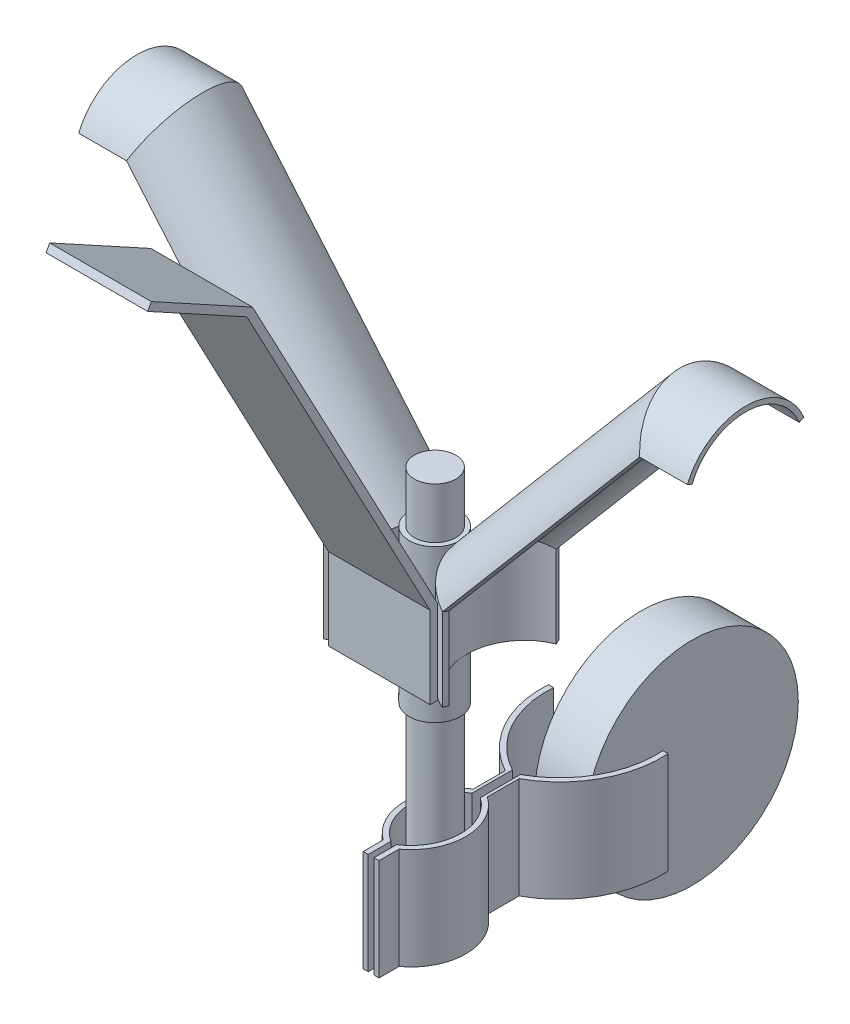
SolidWorks part; units mm, degrees
ref_plane "Front Plane" through (0, 0, 0) normal (0, 0, 1) x (1, 0, 0)
ref_plane "Top Plane" through (0, 0, 0) normal (0, 1, 0) x (1, 0, 0)
ref_plane "Right Plane" through (0, 0, 0) normal (1, 0, 0) x (0, 0, -1)
sketch "Sketch1" plane through (0, 0, 270) normal (0, 0, -1) x (-1, 0, 0)
  line L0 (-59.894, -72.5) -> (-47.401, -72.5)
  line L1 (-59.894, -72.5) -> (59.894, -72.5) construction
  line L2 (-47.401, -72.5) -> (-5, -122.5058)
  line L3 (-5, -122.5058) -> (-5, -141.2421)
  line L4 (0, 0) -> (0, -209.7536) construction
  dimension "D1" = 5
ref_plane "Plane1" through (59.894, -72.5, 270) normal (-1, 0, 0) x (0, 0, 1)
sketch "Sketch2" plane through (59.894, -72.5, 270) normal (-1, 0, 0) x (0, 0, 1)
  line L0 (-11.4645, -6.6719) -> (-10.5401, -7.0533)
  line L1 (11.4645, -6.6719) -> (10.5401, -7.0533)
  arc A0 (-10.5401, -7.0533) -> (10.5401, -7.0533) centre (0, -11.402) cw
  arc A1 (-11.4645, -6.6719) -> (11.4645, -6.6719) centre (0, -11.402) cw
  arc A2 (-2.292, -0.2327) -> (10.5401, -7.0533) centre (0, -11.402) cw construction
  arc A3 (-2.493, 0.7468) -> (11.4645, -6.6719) centre (0, -11.402) cw construction
  point P3 (0, 0)
  dimension "D1" = 1
sweep "Sweep1" add profiles "Sketch2" path "Sketch1"
sketch "Sketch3" plane through (0, 0, 0) normal (1, 0, 0) x (0, 0, -1)
  line L0 (-337.4206, -45.7822) -> (-317.7187, -56.5618)
  line L1 (-317.7187, -56.5618) -> (-281.4645, -124.9537)
  line L2 (-281.4645, -124.9537) -> (-281.4645, -141.2421)
  spline S0 degree 3 poles (-258, -72.5) (-288.1874, -72.5) (-335.6417, -49.6062) (-373.8553, -21.3954) (-386.923, -8.5304) knots -0.01 -0.01 -0.01 -0.01 0.619347 0.99 0.99 0.99 0.99 construction
extrude "Extrude-Thin1" add sketch "Sketch3" along normal mid plane 20 separate body thin thin type mid plane wall 1.5
sketch "Sketch4" plane through (0, -141.2421, 0) normal (0, -1, 0) x (1, 0, 0)
  line L0 (0, 385.5199) -> (0, -463.4767) construction
  circle A0 centre (0, 271.3071) radius 4
  circle A1 centre (0, 271.3071) radius 5
  dimension "D1" = 8
  dimension "D2" = 1
extrude "Boss-Extrude1" add sketch "Sketch4" along normal blind 10 and the other way blind 20
mirror "Mirror1" about plane through (0, 0, 0) normal (1, 0, 0) of "Sweep1"
sketch "Sketch5" plane through (0, -121.2421, 0) normal (0, 1, 0) x (1, 0, 0)
  line L0 (0, -385.5199) -> (0, 463.4767) construction
  circle A0 centre (0, -271.2258) radius 4.0812
extrude "Boss-Extrude2" add sketch "Sketch5" along normal blind 10 and the other way blind 70
sketch "Sketch6" plane through (0, -191.2421, 0) normal (0, -1, 0) x (1, 0, 0)
  line L0 (-11.768, 237.1512) -> (-10.768, 237.1512)
  line L1 (-1.3629, 260.45) -> (-1.3629, 265.95) construction
  line L2 (0, 276.3071) -> (0, 266.3071) construction
  line L3 (0, 385.5199) -> (0, -463.4767) construction
  line L4 (-0.5609, 279.3642) -> (-0.5609, 283.8196)
  line L5 (-0.5609, 283.8196) -> (-1.5609, 283.8196)
  line L6 (-1.5609, 283.8196) -> (-1.5609, 279.8891)
  line L7 (-1.5609, 279.8891) -> (-1.5609, 279.8891)
  line L8 (-1.5609, 279.8891) -> (-1.5609, 279.8891)
  line L9 (-1.5609, 279.8891) -> (-1.5609, 279.8891)
  line L10 (-1.5609, 283.8196) -> (-1.5609, 280.8891) construction
  line L11 (-0.7929, 263.1264) -> (-0.7929, 255.2322)
  line L12 (-1.3629, 262.3048) -> (-1.3629, 256.0539)
  line L13 (11.768, 237.1512) -> (10.768, 237.1512)
  line L14 (1.3628, 262.3048) -> (1.3628, 256.0539)
  line L15 (0.7928, 263.1264) -> (0.7928, 255.2322)
  line L16 (0.5609, 283.8196) -> (1.5609, 283.8196)
  line L17 (1.5609, 283.8196) -> (1.5609, 279.8891)
  line L18 (0.5609, 279.3642) -> (0.5609, 283.8196)
  arc A0 (-0.5609, 279.3642) -> (-0.7929, 263.1264) centre (4.7852, 271.1673) ccw
  circle A1 centre (0, 271.3071) radius 5 construction
  arc A2 (-1.5609, 279.8891) -> (-1.3629, 262.3048) centre (4.7852, 271.1673) ccw
  arc A3 (-0.7929, 255.2322) -> (-10.768, 237.1512) centre (8.3122, 238.4169) ccw
  arc A4 (-1.3629, 256.0539) -> (-11.768, 237.1512) centre (8.2494, 238.4476) ccw
  arc A5 (1.3628, 256.0539) -> (11.768, 237.1512) centre (-8.2494, 238.4476) cw
  arc A6 (0.7928, 255.2322) -> (10.768, 237.1512) centre (-8.3123, 238.4169) cw
  arc A7 (1.5609, 279.8891) -> (1.3628, 262.3048) centre (-4.7853, 271.1673) cw
  arc A8 (0.5609, 279.3642) -> (0.7928, 263.1264) centre (-4.7853, 271.1673) cw
  point P3 (0, 271.3071)
  point P8 (-5, 271.3071)
  point P26 (-1.4128, 258.351)
  point P27 (13.1937, 244.4968)
  point P28 (-1.8799, 258.188)
  point P29 (-0.6851, 255.9061)
  point P30 (-1.3629, 261.0002)
  point P33 (0, 0)
  point P34 (-1.3629, 256.0539)
  point P35 (-4.8904, 236.9325)
  point P36 (-10.768, 237.1512)
  dimension "D1" = 1
  dimension "D3" = 1
  dimension "D5" = 1
  dimension "D2" = 1
  dimension "D4" = 1
extrude "Boss-Extrude3" add sketch "Sketch6" against normal blind 20 separate body contours L12 A4 L0 A3 L11 A0 L4 L5 L6 A2 | A5 L13 A6 L15 A8 L18 L16 L17 A7 L14
sketch "Sketch7" plane through (0, 0, 0) normal (1, 0, 0) x (0, 0, -1)
  circle A0 centre (-225.6725, -181.9308) radius 20.9281
  point P2 (-225.6725, -181.9308)
  point P4 (-237.1512, -181.2421)
extrude "Boss-Extrude4" add sketch "Sketch7" along normal mid plane 10
